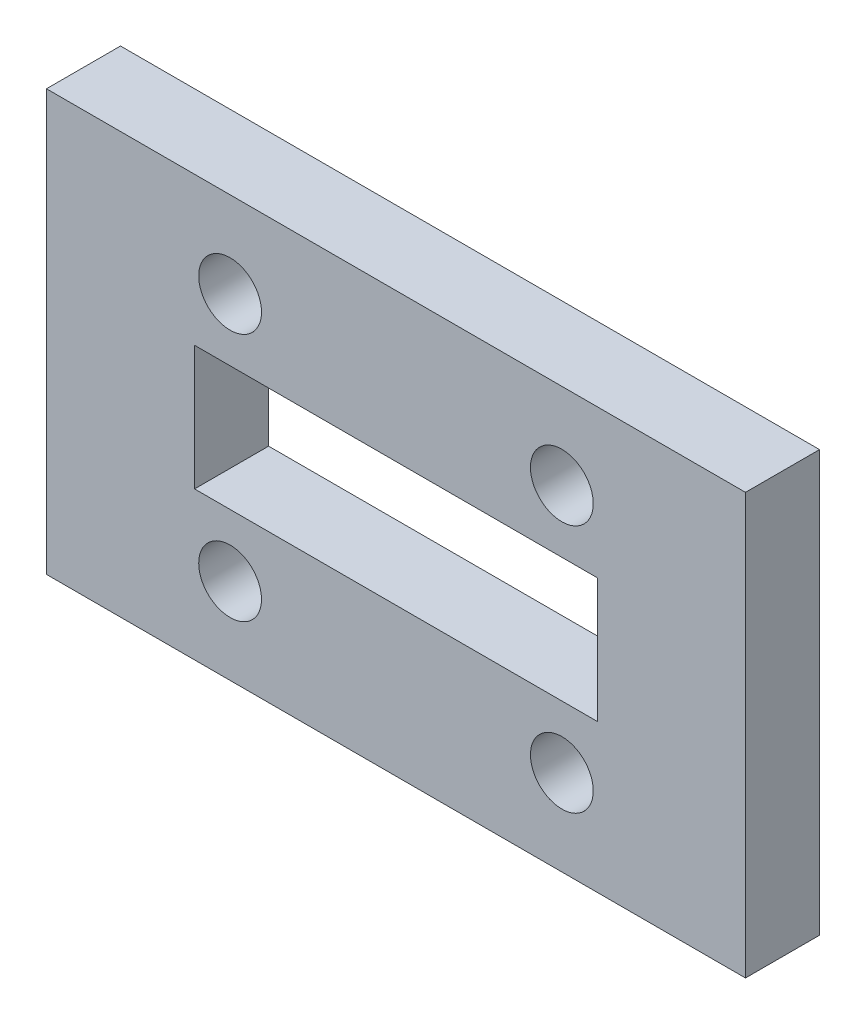
SolidWorks part; units mm, degrees
ref_plane "Front Plane" through (0, 0, 0) normal (0, 0, 1) x (1, 0, 0)
ref_plane "Top Plane" through (0, 0, 0) normal (0, 1, 0) x (1, 0, 0)
ref_plane "Right Plane" through (0, 0, 0) normal (1, 0, 0) x (0, 0, -1)
sketch "Sketch1" plane through (0, 0, 0) normal (0, 0, 1) x (1, 0, 0)
  line L1 (8.636, -2.667) -> (-8.636, -2.667) construction
  line L2 (8.636, -2.667) -> (8.636, 2.667) construction
  line L3 (8.636, 2.667) -> (-8.636, 2.667) construction
  line L4 (-8.636, -2.667) -> (-8.636, 2.667) construction
  line L5 (8.636, -2.667) -> (-8.636, 2.667) construction
  line L6 (8.636, 2.667) -> (-8.636, -2.667) construction
  point P0 (0, 0)
  dimension "D1" = 5.334
  dimension "D2" = 17.272
sketch "Sketch2" plane through (0, 0, 0) normal (0, 0, 1) x (1, 0, 0)
  line L1 (8.636, -2.667) -> (-8.636, -2.667)
  line L2 (8.636, -2.667) -> (8.636, 2.667)
  line L3 (8.636, 2.667) -> (-8.636, 2.667)
  line L4 (-8.636, -2.667) -> (-8.636, 2.667)
  line L5 (8.636, -2.667) -> (-8.636, 2.667) construction
  line L6 (8.636, 2.667) -> (-8.636, -2.667) construction
  line L7 (8.636, -2.667) -> (8.636, 2.667) construction
  line L8 (14.986, -9.017) -> (-14.986, -9.017)
  line L9 (14.986, -9.017) -> (14.986, 9.017)
  line L10 (14.986, 9.017) -> (-14.986, 9.017)
  line L11 (-14.986, -9.017) -> (-14.986, 9.017)
  line L12 (14.986, -9.017) -> (-14.986, 9.017) construction
  line L13 (14.986, 9.017) -> (-14.986, -9.017) construction
  line L14 (8.636, -2.667) -> (-8.636, -2.667) construction
  line L15 (0, 9.017) -> (0, -9.017) construction
  line L16 (-14.986, 0) -> (14.986, 0) construction
  circle A0 centre (-7.112, 5.334) radius 1.3462
  circle A1 centre (7.112, 5.334) radius 1.3462
  circle A2 centre (7.112, -5.334) radius 1.3462
  circle A3 centre (-7.112, -5.334) radius 1.3462
  point P0 (0, 0)
  dimension "D4" = 2.6924
  dimension "D1" = 6.35
  dimension "D2" = 6.35
  dimension "D3" = 7.112
  dimension "D5" = 5.334
extrude "Boss-Extrude1" add sketch "Sketch2" along normal blind 3.175
